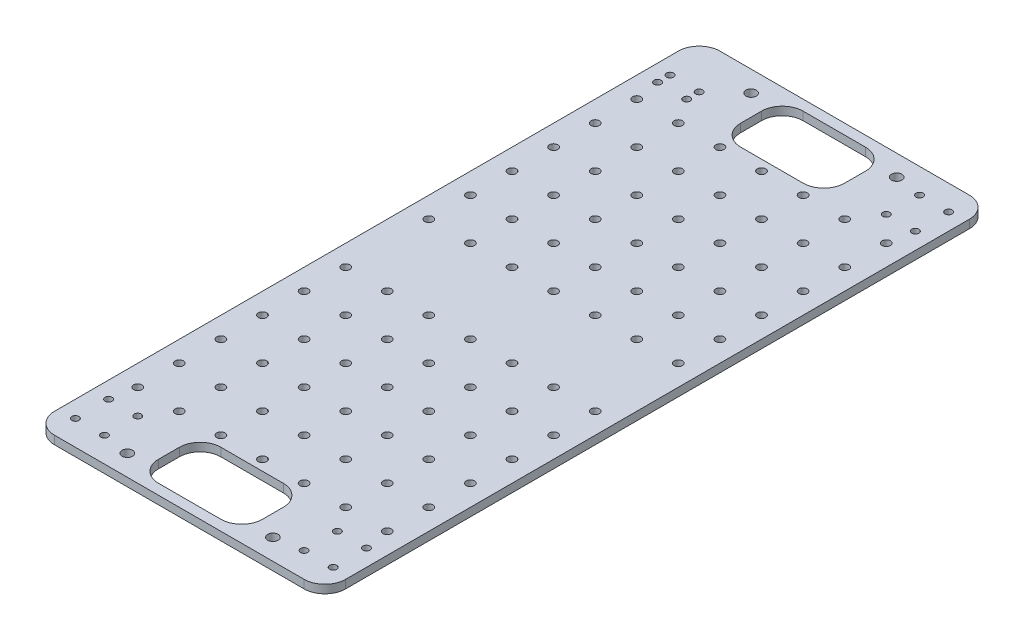
SolidWorks part; units mm, degrees
ref_plane "前视基准面" through (0, 0, 0) normal (0, 0, 1) x (1, 0, 0)
ref_plane "上视基准面" through (0, 0, 0) normal (0, 1, 0) x (1, 0, 0)
ref_plane "右视基准面" through (0, 0, 0) normal (1, 0, 0) x (0, 0, -1)
other "Configuration Table"
sketch "草图1" plane through (0, 0, 0) normal (0, 1, 0) x (1, 0, 0)
  line L0 (-5, 155) -> (5, 155)
  line L1 (-60, -160) -> (60, -160)
  line L2 (-100, -160) -> (-100, 160)
  line L4 (100, -160) -> (100, 160)
  line L5 (-100, -160) -> (100, 160) construction
  line L6 (-100, 160) -> (100, -160) construction
  line L7 (-100, 160) -> (-70, 160)
  line L8 (-100, 160) -> (-100, 120)
  line L9 (-100, 120) -> (-70, 120)
  line L10 (-70, 150) -> (-70, 120)
  line L11 (-60, 160) -> (60, 160)
  line L12 (-70, 160) -> (-70, 153)
  line L13 (-70, 153) -> (-70, 127)
  line L14 (-70, 127) -> (-70, 120)
  line L15 (-70, 153) -> (-40, 153)
  line L16 (-40, 153) -> (-40, 127)
  line L17 (-40, 127) -> (-70, 127)
  line L18 (-70, 153) -> (-70, 148)
  line L19 (-70, 127) -> (-70, 132)
  line L20 (-40, 127) -> (-48, 127)
  line L21 (-48, 127) -> (-48, 132)
  line L22 (-48, 132) -> (-40, 132)
  line L23 (-70, 132) -> (-62, 132)
  line L24 (-62, 132) -> (-62, 127)
  line L25 (-70, 135) -> (-40, 135) construction
  line L28 (-70, 120) -> (0, 120)
  line L29 (100, 120) -> (70, 120)
  line L30 (70, 150) -> (70, 120)
  line L31 (100, -120) -> (70, -120)
  line L32 (70, -150) -> (70, -120)
  line L33 (-70, -150) -> (-70, -120)
  line L34 (-100, -120) -> (-70, -120)
  line L35 (0, 160) -> (0, 140)
  line L36 (-5, 155) -> (5, 155)
  line L37 (-25, 140) -> (-25, 145)
  line L38 (-25, 140) -> (-25, 135)
  line L39 (-15, 125) -> (-5, 125)
  line L40 (-15, 155) -> (-5, 155)
  line L41 (-5, 155) -> (-5, 125)
  line L42 (5, 155) -> (5, 125)
  line L43 (25, 140) -> (25, 135)
  line L44 (15, 125) -> (5, 125)
  line L45 (15, 155) -> (5, 155)
  line L46 (25, 140) -> (25, 145)
  line L47 (15, -125) -> (5, -125)
  line L48 (25, -140) -> (25, -135)
  line L49 (25, -140) -> (25, -145)
  line L50 (15, -155) -> (5, -155)
  line L51 (5, -155) -> (5, -125)
  line L52 (-25, -140) -> (-25, -145)
  line L53 (-25, -140) -> (-25, -135)
  line L54 (-15, -125) -> (-5, -125)
  line L55 (-5, -155) -> (-5, -125)
  line L56 (-15, -155) -> (-5, -155)
  line L57 (-100, 0) -> (-90, 0)
  line L58 (0, 160) -> (0, 140)
  line L59 (0, 160) -> (0, 150)
  line L60 (-70, 120) -> (-70, 0)
  line L61 (70, 120) -> (70, 0)
  line L62 (-70, 0) -> (-70, -120)
  line L63 (70, -120) -> (70, 120)
  line L64 (-5, 125) -> (5, 125)
  line L65 (-5, -125) -> (5, -125)
  line L66 (-5, -155) -> (5, -155)
  line L67 (-70, 0) -> (-60, 0)
  line L68 (100, 160) -> (-100, -160) construction
  line L69 (70, 120) -> (0, 120)
  line L70 (100, -160) -> (-100, 160) construction
  line L71 (-100, 160) -> (100, -160) construction
  circle A0 centre (-62, 132) radius 1.7
  circle A1 centre (-48, 132) radius 1.7
  circle A2 centre (-48, 138) radius 1.7
  circle A3 centre (-62, 138) radius 1.7
  circle A4 centre (48, 148) radius 1.7
  circle A5 centre (48, 132) radius 1.7
  circle A6 centre (62, 132) radius 1.7
  circle A7 centre (62, 148) radius 1.7
  circle A8 centre (62, -148) radius 1.7
  circle A9 centre (62, -132) radius 1.7
  circle A10 centre (48, -132) radius 1.7
  circle A11 centre (48, -148) radius 1.7
  circle A12 centre (-48, -132) radius 1.7
  circle A13 centre (-62, -132) radius 1.7
  circle A14 centre (-48, -148) radius 1.7
  circle A15 centre (-62, -148) radius 1.7
  circle A17 centre (-90, 50) radius 2.5
  circle A18 centre (-90, -50) radius 2.5
  circle A19 centre (90, -50) radius 2.5
  circle A20 centre (90, 0) radius 2.5
  circle A21 centre (90, 50) radius 2.5
  circle A22 centre (0, 150) radius 2.5
  circle A23 centre (35, 150) radius 2.5
  circle A24 centre (-90, 100) radius 2.5
  circle A26 centre (-60, 20) radius 2
  circle A27 centre (-60, 40) radius 2
  circle A28 centre (-60, 60) radius 2
  circle A29 centre (-60, 80) radius 2
  circle A30 centre (-60, 100) radius 2
  circle A31 centre (-60, 120) radius 2
  circle A32 centre (-60, -20) radius 2
  circle A33 centre (-60, -100) radius 2
  circle A34 centre (-60, -80) radius 2
  circle A35 centre (-60, -60) radius 2
  circle A36 centre (-60, -40) radius 2
  circle A37 centre (-60, -120) radius 2
  circle A38 centre (-40, 120) radius 2
  circle A39 centre (-40, 100) radius 2
  circle A40 centre (-40, 80) radius 2
  circle A41 centre (-40, 60) radius 2
  circle A42 centre (-40, 40) radius 2
  circle A43 centre (-40, 20) radius 2
  circle A44 centre (-20, 120) radius 2
  circle A45 centre (-20, 100) radius 2
  circle A46 centre (-20, 80) radius 2
  circle A47 centre (-20, 60) radius 2
  circle A48 centre (-20, 40) radius 2
  circle A49 centre (-20, 20) radius 2
  circle A50 centre (0, 120) radius 2
  circle A51 centre (0, 100) radius 2
  circle A52 centre (0, 80) radius 2
  circle A53 centre (0, 60) radius 2
  circle A54 centre (0, 40) radius 2
  circle A55 centre (0, 20) radius 2
  circle A56 centre (20, 120) radius 2
  circle A57 centre (20, 20) radius 2
  circle A58 centre (20, 40) radius 2
  circle A59 centre (20, 60) radius 2
  circle A60 centre (20, 80) radius 2
  circle A61 centre (20, 100) radius 2
  circle A62 centre (40, 20) radius 2
  circle A63 centre (40, 40) radius 2
  circle A64 centre (40, 60) radius 2
  circle A65 centre (40, 80) radius 2
  circle A66 centre (40, 100) radius 2
  circle A67 centre (40, 120) radius 2
  circle A68 centre (60, 120) radius 2
  circle A69 centre (60, 100) radius 2
  circle A70 centre (60, 80) radius 2
  circle A71 centre (60, 60) radius 2
  circle A72 centre (60, 40) radius 2
  circle A73 centre (60, 20) radius 2
  circle A74 centre (60, -20) radius 2
  circle A75 centre (60, -60) radius 2
  circle A76 centre (60, -80) radius 2
  circle A77 centre (60, -100) radius 2
  circle A78 centre (60, -120) radius 2
  circle A79 centre (40, -120) radius 2
  circle A80 centre (40, -100) radius 2
  circle A81 centre (40, -80) radius 2
  circle A82 centre (40, -60) radius 2
  circle A83 centre (40, -40) radius 2
  circle A84 centre (40, -20) radius 2
  circle A85 centre (20, -100) radius 2
  circle A86 centre (20, -80) radius 2
  circle A87 centre (20, -60) radius 2
  circle A88 centre (20, -40) radius 2
  circle A89 centre (20, -20) radius 2
  circle A90 centre (20, -120) radius 2
  circle A91 centre (0, -20) radius 2
  circle A92 centre (0, -40) radius 2
  circle A93 centre (0, -60) radius 2
  circle A94 centre (0, -80) radius 2
  circle A95 centre (0, -100) radius 2
  circle A96 centre (0, -120) radius 2
  circle A97 centre (-20, -20) radius 2
  circle A98 centre (-20, -40) radius 2
  circle A99 centre (-20, -60) radius 2
  circle A100 centre (-20, -80) radius 2
  circle A101 centre (-20, -100) radius 2
  circle A102 centre (-20, -120) radius 2
  circle A103 centre (-40, -20) radius 2
  circle A104 centre (-40, -40) radius 2
  circle A105 centre (-40, -60) radius 2
  circle A106 centre (-40, -80) radius 2
  circle A107 centre (-40, -100) radius 2
  circle A108 centre (-40, -120) radius 2
  circle A109 centre (-60, -120) radius 2
  circle A110 centre (-60, -100) radius 2
  circle A111 centre (-60, -80) radius 2
  circle A112 centre (-60, -60) radius 2
  circle A113 centre (-60, -40) radius 2
  circle A114 centre (-60, -20) radius 2
  circle A115 centre (60, -40) radius 2
  circle A116 centre (-35, 150) radius 2.5
  circle A117 centre (35, -150) radius 2.5
  circle A118 centre (0, -150) radius 2.5
  circle A119 centre (-35, -150) radius 2.5
  arc A120 (60, -160) -> (70, -150) centre (60, -150) ccw
  arc A121 (-60, -160) -> (-70, -150) centre (-60, -150) cw
  arc A122 (15, -155) -> (25, -145) centre (15, -145) ccw
  arc A123 (25, -135) -> (15, -125) centre (15, -135) ccw
  arc A124 (-15, -125) -> (-25, -135) centre (-15, -135) ccw
  arc A125 (-25, -145) -> (-15, -155) centre (-15, -145) ccw
  arc A126 (-15, 155) -> (-25, 145) centre (-15, 145) ccw
  arc A127 (-25, 135) -> (-15, 125) centre (-15, 135) ccw
  arc A128 (15, 125) -> (25, 135) centre (15, 135) ccw
  arc A129 (15, 155) -> (25, 145) centre (15, 145) cw
  arc A130 (70, 150) -> (60, 160) centre (60, 150) ccw
  arc A131 (-70, 150) -> (-60, 160) centre (-60, 150) cw
  point P0 (0, 0)
  point P14 (-100, 0)
  point P15 (100, 0)
  point P302 (-25, 155)
  point P305 (-25, 125)
  point P312 (70, 160)
  dimension "D12" = 3.4
  dimension "D13" = 3.4
  dimension "D19" = 140
  dimension "D23" = 5
  dimension "D25" = 2
  dimension "D20" = 5
  dimension "D27" = 4
  dimension "D28" = 10
  dimension "D3" = 30
  dimension "D4" = 40
  dimension "D5" = 7
  dimension "D6" = 7
  dimension "D7" = 30
  dimension "D8" = 5
  dimension "D9" = 5
  dimension "D10" = 8
  dimension "D11" = 8
  dimension "D14" = 25
  dimension "D15" = 15
  dimension "D16" = 15
  dimension "D17" = 20
  dimension "D18" = 10
  dimension "D21" = 20
  dimension "D22" = 10
  dimension "D26" = 10
  dimension "D24" = 2
extrude "凸台-拉伸2" add sketch "草图1" along normal blind 4
